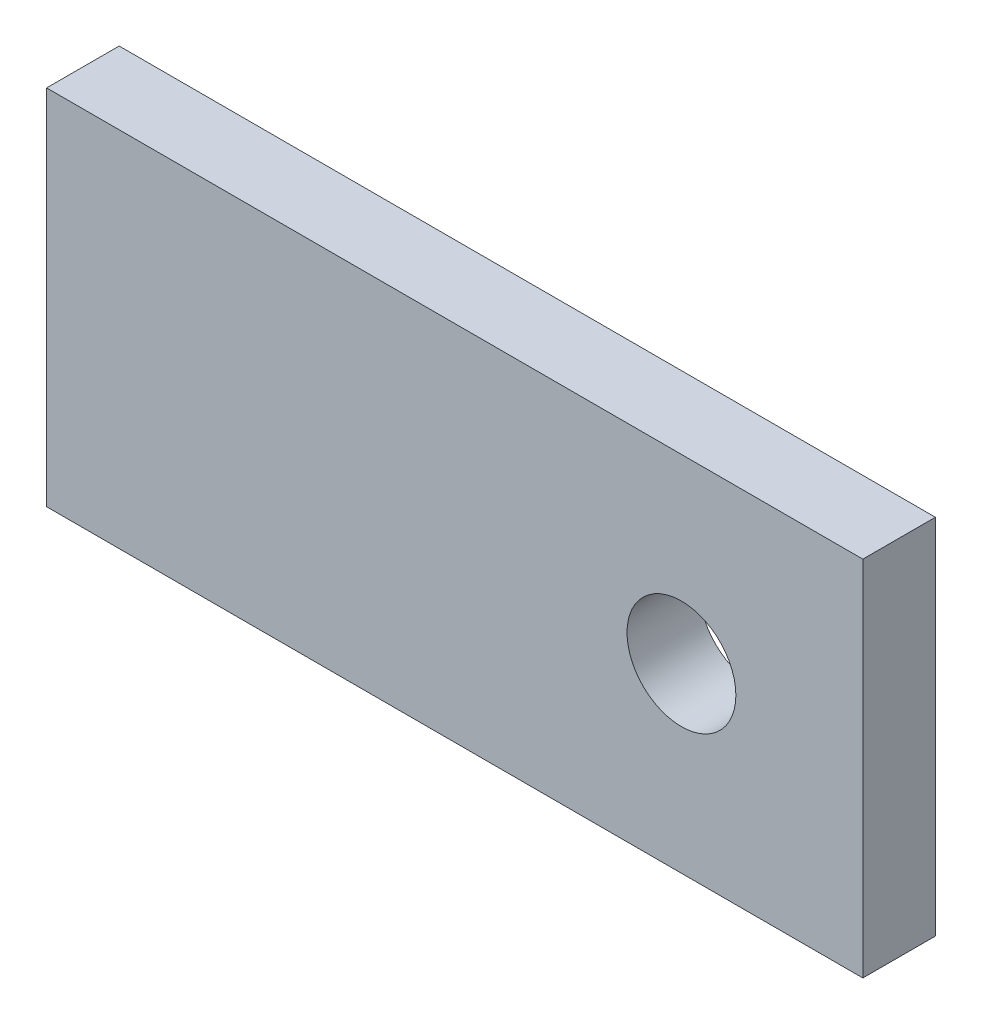
SolidWorks part; units mm, degrees
material "ASTM A36 Steel"
ref_plane "Front Plane" through (0, 0, 0) normal (0, 0, 1) x (1, 0, 0)
ref_plane "Top Plane" through (0, 0, 0) normal (0, 1, 0) x (1, 0, 0)
ref_plane "Right Plane" through (0, 0, 0) normal (1, 0, 0) x (0, 0, -1)
sketch "Sketch1" plane through (0, 0, 0) normal (0, 0, 1) x (1, 0, 0)
  line L1 (40.4082, 11.9388) -> (-49.5918, 11.9388)
  line L2 (40.4082, 11.9388) -> (40.4082, -28.0612)
  line L3 (40.4082, -28.0612) -> (-49.5918, -28.0612)
  line L4 (-49.5918, 11.9388) -> (-49.5918, -28.0612)
  circle A0 centre (20.4082, -8.0612) radius 6
  dimension "D4" = 12
  dimension "D1" = 90
  dimension "D2" = 40
  dimension "D3" = 20
extrude "Boss-Extrude1" add sketch "Sketch1" along normal blind 8
